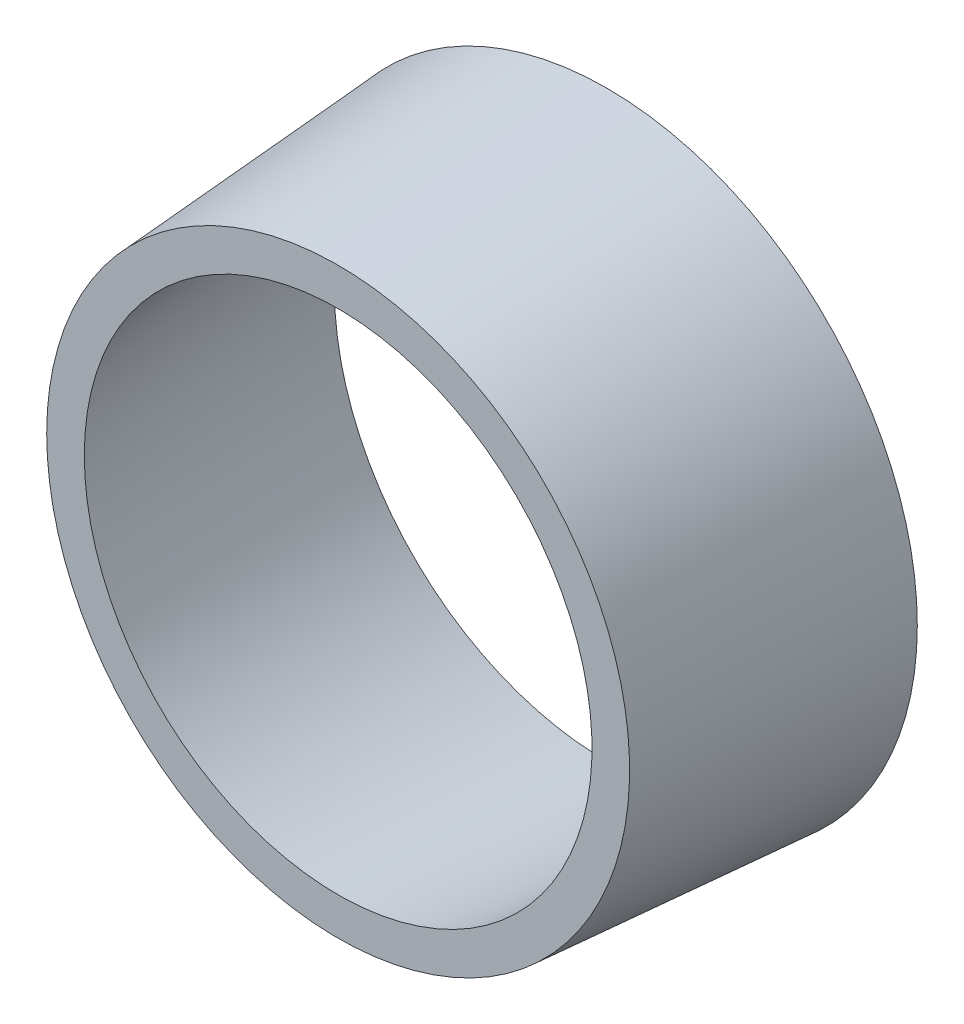
SolidWorks part; units mm, degrees
ref_plane "Front Plane" through (0, 0, 0) normal (1, 0, 0) x (0, 1, 0)
ref_plane "Top Plane" through (0, 0, 0) normal (0, 0, 1) x (0, 1, 0)
ref_plane "Right Plane" through (0, 0, 0) normal (0, 1, 0) x (-1, 0, 0)
sketch "Sketch1" plane through (0, 0, 0) normal (1, 0, 0) x (0, 1, 0)
  line L0 (18.415, 0) -> (20.955, 0)
  line L1 (20.955, 0) -> (19.685, 18.1618)
  line L2 (19.685, 18.1618) -> (17.145, 18.1618)
  line L3 (17.145, 18.1618) -> (18.415, 0)
  line L4 (0, 0) -> (0, 5.1119) construction
  point P3 (0, 0)
  point P8 (0, 0)
  dimension "D1" = 2.54
  dimension "D2" = 4
  dimension "D3" = 18.415
  dimension "D4" = 1.27
revolve "Revolve1" add sketch "Sketch1" angle 360 about L4
